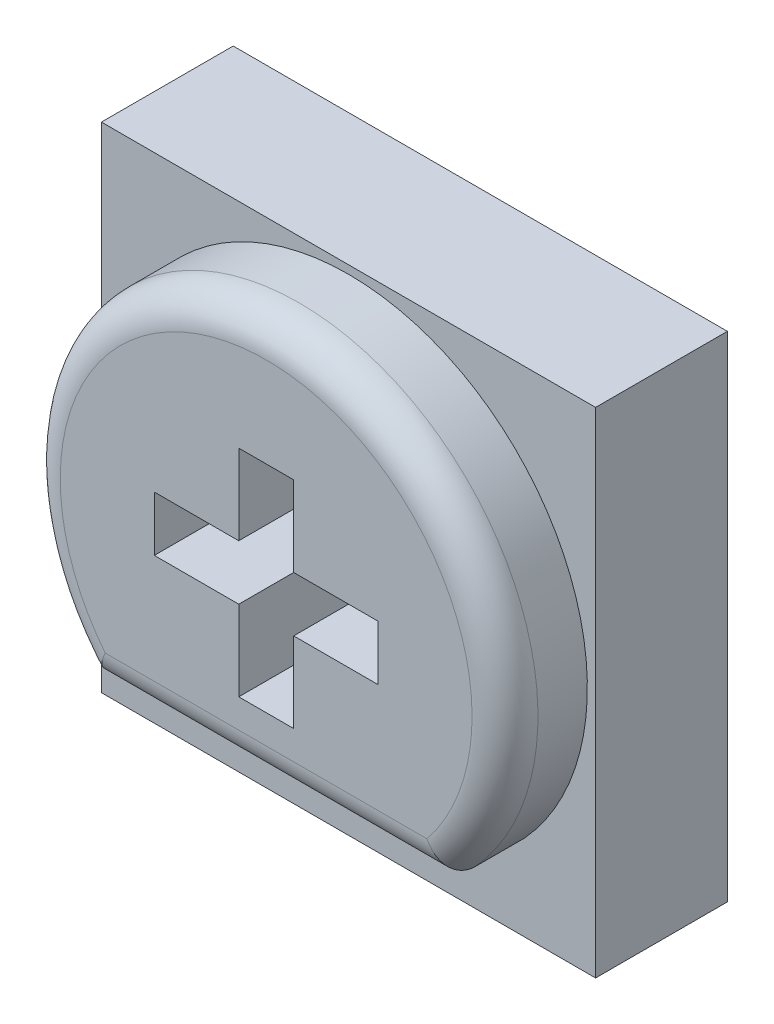
SolidWorks part; units mm, degrees
ref_plane "Front Plane" through (0, 0, 0) normal (0, 0, 1) x (1, 0, 0)
ref_plane "Top Plane" through (0, 0, 0) normal (0, 1, 0) x (1, 0, 0)
ref_plane "Right Plane" through (0, 0, 0) normal (1, 0, 0) x (0, 0, -1)
sketch "Sketch1" plane through (0, 0, 0) normal (0, 0, 1) x (1, 0, 0)
  line L1 (-1.5, 1.5) -> (1.5, 1.5)
  line L2 (-1.5, 1.5) -> (-1.5, -1.5)
  line L3 (-1.5, -1.5) -> (1.5, -1.5)
  line L4 (1.5, 1.5) -> (1.5, -1.5)
  line L5 (-1.5, 1.5) -> (1.5, -1.5) construction
  line L6 (-1.5, -1.5) -> (1.5, 1.5) construction
  point P0 (0, 0)
  dimension "D1" = 3
  dimension "D2" = 3
extrude "Boss-Extrude1" add sketch "Sketch1" along normal blind 0.8
sketch "Sketch2" plane through (0, 0, 0.8) normal (0, 0, 1) x (1, 0, 0)
  line L0 (-1.0686, -0.9801) -> (1.0686, -0.9801)
  arc A0 (1.0686, -0.9801) -> (-1.0686, -0.9801) centre (0, 0) ccw
  dimension "D1" = 2.9
extrude "Boss-Extrude2" add sketch "Sketch2" along normal blind 0.5
sketch "Sketch3" plane through (0, 0, 1.3) normal (0, 0, 1) x (1, 0, 0)
  text T0 "+" font "Century Gothic" height 2
extrude "Cut-Extrude1" cut sketch "Sketch3" against normal blind 0.8
fillet "Fillet1" radius 0.2 2 edges at (0, -0.9801, 1.3) (0, 1.45, 1.3)
